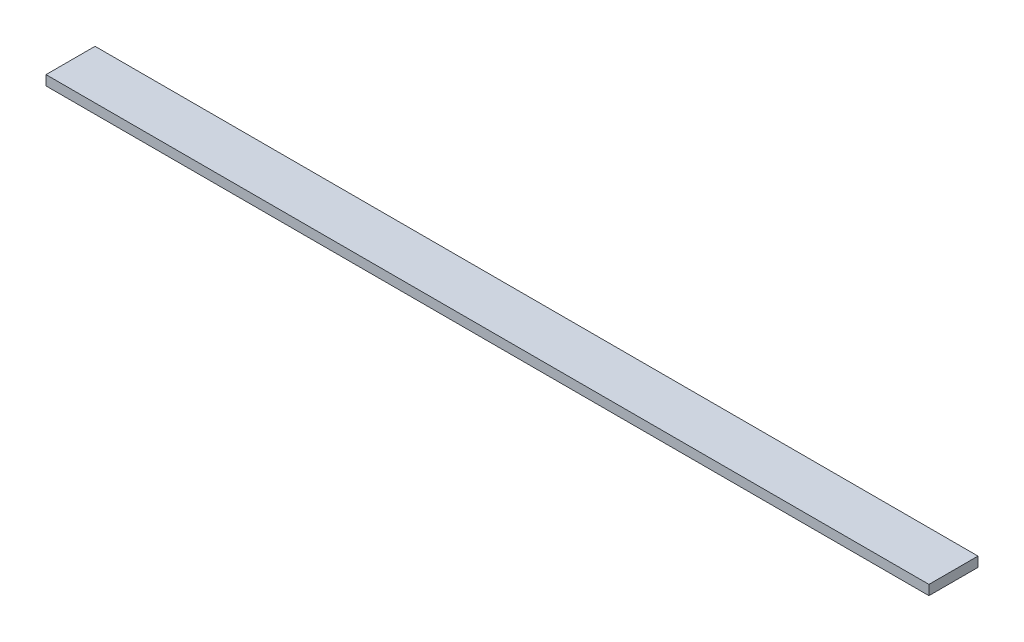
SolidWorks part; units mm, degrees
ref_plane "Front Plane" through (0, 0, 0) normal (0, 0, 1) x (1, 0, 0)
ref_plane "Top Plane" through (0, 0, 0) normal (0, 1, 0) x (1, 0, 0)
ref_plane "Right Plane" through (0, 0, 0) normal (1, 0, 0) x (0, 0, -1)
sketch "Sketch1" plane through (0, 0, 0) normal (0, 1, 0) x (1, 0, 0)
  line L1 (-261.0837, 173.4233) -> (119.9163, 173.4233)
  line L2 (-261.0837, 173.4233) -> (-261.0837, -207.5767)
  line L3 (-261.0837, -207.5767) -> (119.9163, -207.5767)
  line L4 (119.9163, 173.4233) -> (119.9163, -207.5767)
  dimension "D1" = 381
  dimension "D2" = 381
extrude "Boss-Extrude1" add sketch "Sketch1" along normal blind 25.4
fillet "Fillet1" radius 25.4 4 edges at (-261.0837, 12.7, -173.4233) (-261.0837, 12.7, 207.5767) (119.9163, 12.7, 207.5767) (119.9163, 12.7, -173.4233)
sketch "Sketch2" plane through (0, 25.4, 0) normal (0, 1, 0) x (1, 0, 0)
  line L0 (94.5163, 173.4233) -> (-235.6837, 173.4233) construction
  line L1 (-261.0837, 148.0233) -> (-261.0837, -182.1767) construction
  line L2 (-70.5837, 173.4233) -> (-70.5837, -207.5767) construction
  line L3 (-235.6837, -207.5767) -> (94.5163, -207.5767) construction
  line L4 (119.9163, -17.0767) -> (-261.0837, -17.0767) construction
  line L5 (119.9163, -182.1767) -> (119.9163, 148.0233) construction
  line L6 (119.9163, -182.1767) -> (119.9163, 148.0233)
  line L7 (94.5163, 173.4233) -> (-235.6837, 173.4233)
  line L8 (110.3569, 127.9428) -> (74.4359, 163.8639)
  line L9 (74.4359, 163.8639) -> (89.8833, 163.8639)
  line L10 (110.3569, 127.9428) -> (110.3569, 143.3902)
  line L11 (-251.5242, 127.9428) -> (-251.5242, 143.3902)
  line L12 (-215.6032, 163.8639) -> (-231.0506, 163.8639)
  line L13 (-251.5242, -162.0962) -> (-251.5242, -177.5436)
  line L14 (-215.6032, -198.0173) -> (-231.0506, -198.0173)
  line L15 (110.3569, -162.0962) -> (74.4359, -198.0173)
  line L16 (110.3569, -162.0962) -> (110.3569, -177.5436)
  line L17 (74.4359, -198.0173) -> (89.8833, -198.0173)
  arc A0 (-223.3269, 163.8639) -> (-251.5242, 135.6665) centre (-227.0386, 139.3782) ccw
  arc A2 (75.1102, 173.4233) -> (119.9163, 128.6172) centre (112.4768, 165.9838) ccw
  arc A3 (-216.2776, 173.4233) -> (-261.0837, 128.6172) centre (-253.6442, 165.9838) cw
  arc A4 (-223.3269, -198.0173) -> (-251.5242, -169.8199) centre (-227.0386, -173.5316) cw
  arc A5 (119.9163, 148.0233) -> (94.5163, 173.4233) centre (94.5163, 148.0233) ccw construction
  arc A6 (119.9163, 148.0233) -> (94.5163, 173.4233) centre (94.5163, 148.0233) ccw
  circle A8 centre (112.4768, 165.9838) radius 38.1
  arc A11 (82.1596, 163.8639) -> (110.3569, 135.6665) centre (85.8712, 139.3782) cw
  arc A12 (-216.2776, -207.5767) -> (-261.0837, -162.7706) centre (-253.6442, -200.1372) ccw
  arc A13 (82.1596, -198.0173) -> (110.3569, -169.8199) centre (85.8712, -173.5316) ccw
  arc A14 (75.1102, -207.5767) -> (119.9163, -162.7706) centre (112.4768, -200.1372) cw
  dimension "D1" = 50.8
  dimension "D2" = 135
extrude "Boss-Extrude2" add sketch "Sketch2" along normal blind 127
fillet "Fillet5" radius 2.54 4 edges at (119.9163, 88.9, -128.6172) (110.3569, 88.9, -127.9428) (74.4359, 88.9, -163.8639) (75.1102, 88.9, -173.4233)
fillet "Fillet6" radius 2.54 12 edges at (-215.6032, 88.9, -163.8639) (-216.2776, 88.9, -173.4233) (-251.5242, 88.9, -127.9428) (-261.0837, 88.9, -128.6172) (-216.2776, 88.9, 207.5767) (-215.6032, 88.9, 198.0173) (-261.0837, 88.9, 162.7706) (-251.5242, 88.9, 162.0962) (74.4359, 88.9, 198.0173) (75.1102, 88.9, 207.5767) (110.3569, 88.9, 162.0962) (119.9163, 88.9, 162.7706)
sketch "Sketch3" plane through (0, 152.4, 0) normal (0, 1, 0) x (1, 0, 0)
  line L0 (-261.0837, -164.9164) -> (-261.0837, -182.1767) construction
  line L1 (-261.0837, -207.5767) -> (119.9163, -207.5767)
  line L2 (-261.0837, -207.5767) -> (-261.0837, -162.0399)
  line L3 (-261.0837, -162.0399) -> (119.9163, -162.0399)
  line L4 (119.9163, -207.5767) -> (119.9163, -162.0399)
  line L5 (-235.6837, -207.5767) -> (-218.4233, -207.5767) construction
  dimension "D1" = 381
extrude "Boss-Extrude3" add sketch "Sketch3" along normal blind 127
sketch "Sketch5" plane through (0, 152.4, 0) normal (0, -1, 0) x (1, 0, 0)
  line L0 (-261.0837, 162.0399) -> (-261.0837, 164.9164) construction
  line L1 (-254.0942, 162.0399) -> (-261.0837, 162.0399) construction
  line L2 (-261.0837, 207.5767) -> (-235.6837, 207.5767) construction
  line L3 (-261.0837, 182.1767) -> (-261.0837, 207.5767) construction
  line L4 (-261.0837, 162.0399) -> (-261.0837, 164.9164)
  line L5 (-254.0942, 162.0399) -> (-261.0837, 162.0399)
  line L6 (-261.0837, 207.5767) -> (-235.6837, 207.5767)
  line L7 (-261.0837, 182.1767) -> (-261.0837, 207.5767)
  arc A0 (-261.0837, 164.9164) -> (-258.8936, 162.4006) centre (-258.5437, 164.9164) ccw construction
  arc A1 (-258.8936, 162.4006) -> (-254.0942, 162.0399) centre (-253.6442, 200.1372) ccw construction
  arc A2 (-235.6837, 207.5767) -> (-261.0837, 182.1767) centre (-235.6837, 182.1767) ccw construction
  arc A3 (-261.0837, 164.9164) -> (-258.8936, 162.4006) centre (-258.5437, 164.9164) ccw
  arc A4 (-258.8936, 162.4006) -> (-254.0942, 162.0399) centre (-253.6442, 200.1372) ccw
  arc A5 (-235.6837, 207.5767) -> (-261.0837, 182.1767) centre (-235.6837, 182.1767) ccw
extrude "Cut-Extrude1" cut sketch "Sketch5" against normal blind 127
sketch "Sketch6" plane through (0, 152.4, 0) normal (0, -1, 0) x (1, 0, 0)
  line L0 (119.9163, 162.0399) -> (112.9269, 162.0399) construction
  line L1 (119.9163, 164.9164) -> (119.9163, 162.0399) construction
  line L2 (119.9163, 207.5767) -> (119.9163, 182.1767) construction
  line L3 (94.5163, 207.5767) -> (119.9163, 207.5767) construction
  line L4 (119.9163, 162.0399) -> (112.9269, 162.0399)
  line L5 (119.9163, 164.9164) -> (119.9163, 162.0399)
  line L6 (119.9163, 207.5767) -> (119.9163, 182.1767)
  line L7 (94.5163, 207.5767) -> (119.9163, 207.5767)
  arc A0 (112.9269, 162.0399) -> (117.7263, 162.4006) centre (112.4768, 200.1372) ccw construction
  arc A1 (117.7263, 162.4006) -> (119.9163, 164.9164) centre (117.3763, 164.9164) ccw construction
  arc A2 (119.9163, 182.1767) -> (94.5163, 207.5767) centre (94.5163, 182.1767) ccw construction
  arc A3 (112.9269, 162.0399) -> (117.7263, 162.4006) centre (112.4768, 200.1372) ccw
  arc A4 (117.7263, 162.4006) -> (119.9163, 164.9164) centre (117.3763, 164.9164) ccw
  arc A5 (119.9163, 182.1767) -> (94.5163, 207.5767) centre (94.5163, 182.1767) ccw
extrude "Cut-Extrude2" cut sketch "Sketch6" against normal blind 127
sketch "Sketch7" plane through (0, 0, 207.5767) normal (0, 0, 1) x (1, 0, 0)
  line L0 (-218.4233, 152.4) -> (77.256, 152.4) construction
  line L1 (-197.3962, 152.4) -> (-356.9891, 152.4)
  line L2 (-197.3962, 152.4) -> (-197.3962, -127.2684)
  line L3 (-197.3962, -127.2684) -> (-356.9891, -127.2684)
  line L4 (-356.9891, 152.4) -> (-356.9891, -127.2684)
  line L6 (-197.3962, 152.4) -> (188.2054, 152.4)
  line L7 (-197.3962, 152.4) -> (-197.3962, -138.9301)
  line L8 (-197.3962, -138.9301) -> (188.2054, -138.9301)
  line L9 (188.2054, 152.4) -> (188.2054, -138.9301)
extrude "Cut-Extrude3" cut sketch "Sketch7" against normal through all contours L6 L3 L0 L2 L8 L4 | L2 L0 L3 | L9 L6 L4 L8 L2 L7 | L1 L4 L3 L2 L8 L7 | L2 L0 L1 L7 L8 | L2 L1 L0
sketch "Sketch9" plane through (0, 279.4, 0) normal (0, 1, 0) x (1, 0, 0)
  line L4 (112.9269, -162.0399) -> (-254.0942, -162.0399)
  line L5 (-261.0837, -164.9164) -> (-261.0837, -182.1767)
  line L6 (-235.6837, -207.5767) -> (94.5163, -207.5767)
  line L7 (119.9163, -182.1767) -> (119.9163, -164.9164)
  line L8 (112.9269, -162.0399) -> (-254.0942, -162.0399)
  line L9 (-261.0837, -164.9164) -> (-261.0837, -182.1767)
  line L10 (-235.6837, -207.5767) -> (94.5163, -207.5767)
  line L11 (119.9163, -182.1767) -> (119.9163, -164.9164)
  arc A6 (119.9163, -164.9164) -> (117.7263, -162.4006) centre (117.3763, -164.9164) ccw
  arc A7 (117.7263, -162.4006) -> (112.9269, -162.0399) centre (112.4768, -200.1372) ccw
  arc A8 (-254.0942, -162.0399) -> (-258.8936, -162.4006) centre (-253.6442, -200.1372) ccw
  arc A9 (-258.8936, -162.4006) -> (-261.0837, -164.9164) centre (-258.5437, -164.9164) ccw
  arc A10 (-261.0837, -182.1767) -> (-235.6837, -207.5767) centre (-235.6837, -182.1767) ccw
  arc A11 (94.5163, -207.5767) -> (119.9163, -182.1767) centre (94.5163, -182.1767) ccw
  arc A12 (119.9163, -164.9164) -> (117.7263, -162.4006) centre (117.3763, -164.9164) ccw
  arc A13 (117.7263, -162.4006) -> (112.9269, -162.0399) centre (112.4768, -200.1372) ccw
  arc A14 (-254.0942, -162.0399) -> (-258.8936, -162.4006) centre (-253.6442, -200.1372) ccw
  arc A15 (-258.8936, -162.4006) -> (-261.0837, -164.9164) centre (-258.5437, -164.9164) ccw
  arc A16 (-261.0837, -182.1767) -> (-235.6837, -207.5767) centre (-235.6837, -182.1767) ccw
  arc A17 (94.5163, -207.5767) -> (119.9163, -182.1767) centre (94.5163, -182.1767) ccw
  dimension "D1" = 0
extrude "Cut-Extrude4" cut sketch "Sketch9" against normal blind 121.92
sketch "Sketch10" plane through (0, 157.48, 0) normal (0, 1, 0) x (1, 0, 0)
  line L0 (112.9269, -162.0399) -> (-254.0942, -162.0399) construction
  line L1 (-248.2533, -162.0399) -> (-261.0837, -162.0399)
  line L2 (-248.2533, -162.0399) -> (-248.2533, -167.4209)
  line L3 (-248.2533, -167.4209) -> (-261.0837, -167.4209)
  line L4 (-261.0837, -162.0399) -> (-261.0837, -167.4209)
  line L5 (-261.0837, -164.9164) -> (-261.0837, -182.1767) construction
  line L6 (119.9163, -182.1767) -> (119.9163, -164.9164) construction
  line L7 (107.7264, -162.0399) -> (119.9163, -162.0399)
  line L8 (107.7264, -162.0399) -> (107.7264, -169.5931)
  line L9 (107.7264, -169.5931) -> (119.9163, -169.5931)
  line L10 (119.9163, -162.0399) -> (119.9163, -169.5931)
extrude "Boss-Extrude4" add sketch "Sketch10" against normal blind 5.08
sketch "Sketch12" plane through (0, 0, 162.0399) normal (0, 0, -1) x (-1, 0, 0)
  line L0 (261.0837, 152.4) -> (261.0837, 157.48) construction
  line L1 (-119.9163, 157.48) -> (261.0837, 157.48) construction
  line L2 (-119.9163, 152.4) -> (-119.9163, 157.48) construction
  line L3 (-119.9163, 152.4) -> (261.0837, 152.4) construction
  line L4 (261.0837, 152.4) -> (261.0837, 157.48)
  line L5 (-119.9163, 157.48) -> (261.0837, 157.48)
  line L6 (-119.9163, 152.4) -> (-119.9163, 157.48)
  line L7 (-119.9163, 152.4) -> (261.0837, 152.4)
extrude "Boss-Extrude5" add sketch "Sketch12" along normal blind 5.842
sketch "Sketch13" plane through (0, 157.48, 0) normal (0, 1, 0) x (1, 0, 0)
  line L4 (-235.6837, -207.5767) -> (94.5163, -207.5767)
  line L5 (119.9163, -182.1767) -> (119.9163, -156.1979)
  line L6 (119.9163, -156.1979) -> (-261.0837, -156.1979)
  line L7 (-261.0837, -156.1979) -> (-261.0837, -182.1767)
  line L9 (119.9163, -182.1767) -> (119.9163, -156.1979)
  line L10 (119.9163, -156.1979) -> (-261.0837, -156.1979)
  line L11 (-261.0837, -156.1979) -> (-261.0837, -182.1767)
  line L12 (-235.6837, -207.5767) -> (94.5163, -207.5767)
  arc A2 (-261.0837, -182.1767) -> (-235.6837, -207.5767) centre (-235.6837, -182.1767) ccw
  arc A3 (-261.0837, -182.1767) -> (-235.6837, -207.5767) centre (-235.6837, -182.1767) ccw
  arc A4 (94.5163, -207.5767) -> (119.9163, -182.1767) centre (94.5163, -182.1767) ccw
  arc A5 (94.5163, -207.5767) -> (119.9163, -182.1767) centre (94.5163, -182.1767) ccw
  dimension "D1" = 0
sketch "Sketch14" plane through (0, 157.48, 0) normal (0, 1, 0) x (1, 0, 0)
  line L1 (119.9163, -182.1767) -> (94.5163, -182.1767)
  line L2 (119.9163, -182.1767) -> (119.9163, -207.5767)
  line L3 (119.9163, -207.5767) -> (94.5163, -207.5767)
  line L4 (94.5163, -182.1767) -> (94.5163, -207.5767)
  line L5 (-235.6837, -207.5767) -> (-261.0837, -207.5767)
  line L6 (-235.6837, -207.5767) -> (-235.6837, -182.1767)
  line L7 (-235.6837, -182.1767) -> (-261.0837, -182.1767)
  line L8 (-261.0837, -207.5767) -> (-261.0837, -182.1767)
extrude "Boss-Extrude6" add sketch "Sketch14" against normal up to surface (5.08 mm away) up to face at (-70.5837, 152.4, 183.7373)
sketch "Sketch15" plane through (0, 157.48, 0) normal (0, 1, 0) x (1, 0, 0)
  line L0 (-261.0837, -156.1979) -> (-261.0837, -207.5767) construction
  line L1 (119.9163, -207.5767) -> (-261.0837, -207.5767)
  line L2 (119.9163, -207.5767) -> (119.9163, -182.1767)
  line L3 (119.9163, -182.1767) -> (-261.0837, -182.1767)
  line L4 (-261.0837, -207.5767) -> (-261.0837, -182.1767)
  dimension "D1" = 25.4
extrude "Boss-Extrude7" add sketch "Sketch15" along normal blind 2.54
sketch "Sketch18" plane through (-261.0837, 0, 0) normal (-1, 0, 0) x (0, 0, 1)
  line L1 (182.1767, 157.48) -> (156.1979, 157.48)
  line L2 (182.1767, 157.48) -> (182.1767, 152.4)
  line L3 (182.1767, 152.4) -> (156.1979, 152.4)
  line L4 (156.1979, 157.48) -> (156.1979, 152.4)
extrude "Cut-Extrude6" cut sketch "Sketch18" against normal through all
sketch "Sketch19" plane through (-261.0837, 0, 0) normal (-1, 0, 0) x (0, 0, 1)
  line L0 (207.5767, 152.4) -> (207.5767, 160.02) construction
  line L2 (182.1767, 154.94) -> (182.1767, 149.86)
  line L3 (182.1767, 149.86) -> (207.5767, 149.86)
  line L4 (207.5767, 154.94) -> (207.5767, 149.86)
  line L5 (207.5767, 154.94) -> (182.1767, 154.94)
  line L6 (207.5767, 149.86) -> (182.1767, 149.86)
  line L7 (207.5767, 149.86) -> (207.5767, 152.4)
  line L8 (207.5767, 152.4) -> (182.1767, 152.4)
  line L9 (182.1767, 149.86) -> (182.1767, 152.4)
  line M2 (182.1767, 160.02) -> (182.1767, 152.4)
  line M3 (182.1767, 152.4) -> (207.5767, 152.4)
  line M4 (207.5767, 152.4) -> (207.5767, 160.02)
extrude "Cut-Extrude7" cut sketch "Sketch19" against normal through all contours L5 M4 M2 M3
sketch "Sketch21" plane through (0, 160.02, 0) normal (0, 1, 0) x (1, 0, 0)
  line L1 (-261.0837, -182.1767) -> (-337.2837, -182.1767)
  line L2 (-261.0837, -182.1767) -> (-261.0837, -207.5767)
  line L3 (-261.0837, -207.5767) -> (-337.2837, -207.5767)
  line L4 (-337.2837, -182.1767) -> (-337.2837, -207.5767)
  dimension "D1" = 76.2
extrude "Boss-Extrude8" add sketch "Sketch21" against normal up to surface (5.08 mm away) up to face at (-70.5837, 154.94, 194.8767)
sketch "Sketch22" plane through (0, 0, 182.1767) normal (0, 0, -1) x (-1, 0, 0)
  line L4 (-119.9163, 160.02) -> (-119.9163, 154.94)
  line L5 (-119.9163, 154.94) -> (337.2837, 154.94)
  line L6 (337.2837, 154.94) -> (337.2837, 160.02)
  line L7 (337.2837, 160.02) -> (-119.9163, 160.02)
  line L8 (-119.9163, 160.02) -> (-119.9163, 154.94)
  line L9 (-119.9163, 154.94) -> (337.2837, 154.94)
  line L10 (337.2837, 154.94) -> (337.2837, 160.02)
  line L11 (337.2837, 160.02) -> (-119.9163, 160.02)
  dimension "D1" = 0
